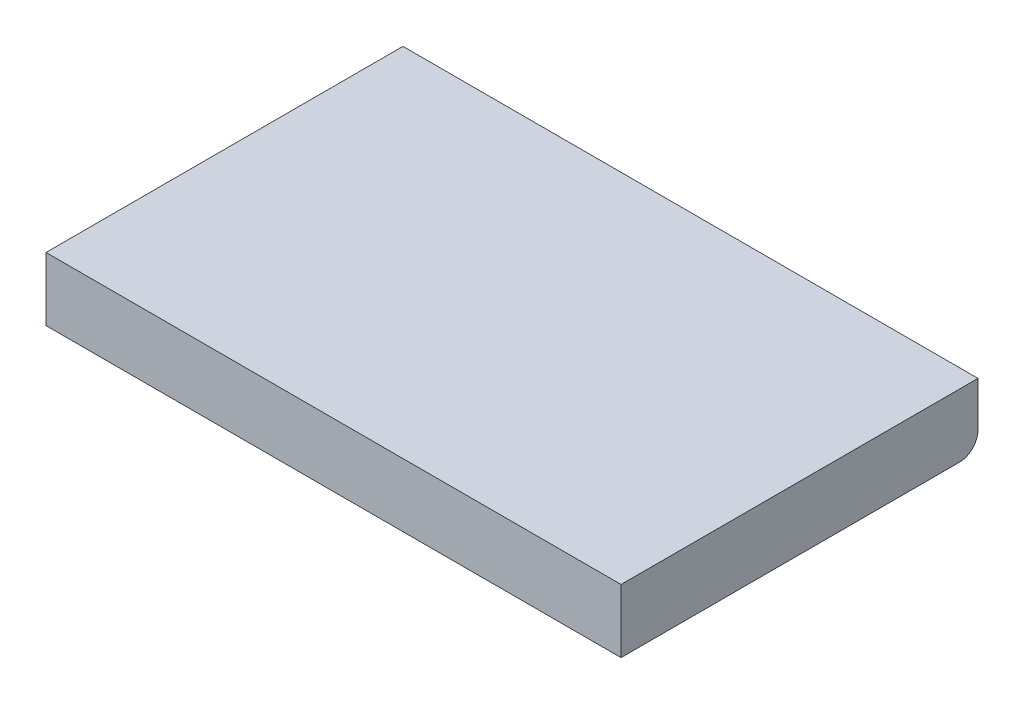
SolidWorks part; units mm, degrees
ref_plane "Front Plane" through (0, 0, 0) normal (0, 0, 1) x (1, 0, 0)
ref_plane "Top Plane" through (0, 0, 0) normal (0, 1, 0) x (1, 0, 0)
ref_plane "Right Plane" through (0, 0, 0) normal (1, 0, 0) x (0, 0, -1)
sketch "Çizim1" plane through (0, 0, 0) normal (0, 1, 0) x (1, 0, 0)
  line L1 (-79.1, 49.1) -> (79.1, 49.1)
  line L2 (-79.1, 49.1) -> (-79.1, -49.1)
  line L3 (-79.1, -49.1) -> (79.1, -49.1)
  line L4 (79.1, 49.1) -> (79.1, -49.1)
  line L5 (-79.1, 49.1) -> (79.1, -49.1) construction
  line L6 (-79.1, -49.1) -> (79.1, 49.1) construction
  point P0 (0, 0)
  dimension "D1" = 158.2
  dimension "D2" = 98.2
extrude "Yükseklik-Ekstrüzyon1" add sketch "Çizim1" along normal blind 6.35
ref_plane "Düzlem1" through (-47.096, 0, 0) normal (1, 0, 0) x (0, 0, -1)
ref_plane "Düzlem2" through (47.096, 0, 0) normal (-1, 0, 0) x (0, 0, 1)
sketch "Çizim2" plane through (-47.096, 0, 0) normal (1, 0, 0) x (0, 0, -1)
  line L0 (49.1, 0) -> (42.75, 0)
  line L1 (49.1, 0) -> (49.1, -2.7997)
  line L2 (42.75, 0) -> (42.75, -2.7997)
  arc A0 (42.75, -2.7997) -> (49.1, -2.7997) centre (45.925, -5.5365) ccw
  dimension "D1" = 6.35
  dimension "D2" = 3.175
extrude "Yükseklik-Ekstrüzyon2" add sketch "Çizim2" along normal blind 34.142
sketch "Çizim3" plane through (47.096, 0, 0) normal (-1, 0, 0) x (0, 0, 1)
  line L0 (-42.75, 0) -> (-49.1, 0)
  line L1 (-42.75, 0) -> (-42.75, -2.7997)
  line L2 (-49.1, 0) -> (-49.1, -2.7997)
  arc A0 (-49.1, -2.7997) -> (-42.75, -2.7997) centre (-45.925, -5.5365) ccw
extrude "Yükseklik-Ekstrüzyon3" add sketch "Çizim3" along normal blind 34.65
sketch "Çizim5" plane through (47.096, 0, 0) normal (1, 0, 0) x (0, 0, -1)
  circle A0 centre (45.925, -5.5365) radius 1.651
extrude "Kes-Ekstrüzyon1" cut sketch "Çizim5" against normal blind 38.1
sketch "Çizim6" plane through (-47.096, 0, 0) normal (-1, 0, 0) x (0, 0, 1)
  circle A0 centre (-45.925, -5.5365) radius 1.651
extrude "Kes-Ekstrüzyon2" cut sketch "Çizim6" against normal blind 34.142
sketch "Çizim7" plane through (-79.1, 0, 0) normal (-1, 0, 0) x (0, 0, 1)
  line L1 (49.1, 0) -> (-49.1, 0)
  line L2 (49.1, 0) -> (49.1, -11.08)
  line L3 (49.1, -11.08) -> (-49.1, -11.08)
  line L4 (-49.1, 0) -> (-49.1, -11.08)
  dimension "D1" = 11.08
extrude "Yükseklik-Ekstrüzyon4" add sketch "Çizim7" against normal blind 6.35
sketch "Çizim10" plane through (79.1, 0, 0) normal (1, 0, 0) x (0, 0, -1)
  line L1 (-49.1, 0) -> (49.1, 0)
  line L2 (-49.1, 0) -> (-49.1, -11.08)
  line L3 (-49.1, -11.08) -> (49.1, -11.08)
  line L4 (49.1, 0) -> (49.1, -11.08)
extrude "Yükseklik-Ekstrüzyon5" add sketch "Çizim10" against normal blind 6.35
sketch "Çizim12" plane through (0, 0, 49.1) normal (0, 0, 1) x (1, 0, 0)
  line L1 (-72.75, 0) -> (72.75, 0)
  line L2 (-72.75, 0) -> (-72.75, -11.08)
  line L3 (-72.75, -11.08) -> (72.75, -11.08)
  line L4 (72.75, 0) -> (72.75, -11.08)
extrude "Yükseklik-Ekstrüzyon6" add sketch "Çizim12" against normal blind 6.35
fillet "Radyus1" radius 5.08 1 edges at (75.925, -11.08, -49.1)
fillet "Radyus2" radius 5.08 1 edges at (-75.925, -11.08, -49.1)
sketch "Çizim15" plane through (-79.1, 0, 0) normal (-1, 0, 0) x (0, 0, 1)
  circle A0 centre (-45.925, -5.5365) radius 1.651
extrude "Kes-Ekstrüzyon3" cut sketch "Çizim15" against normal blind 6.35
